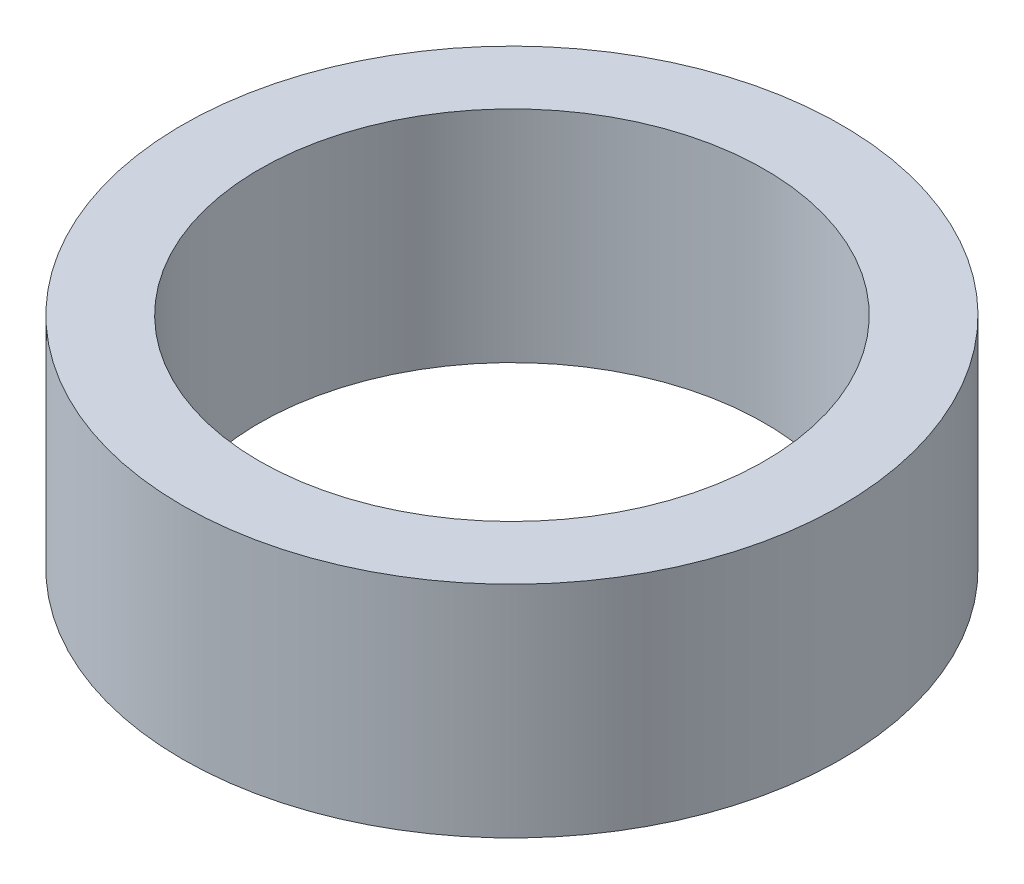
SolidWorks part; units mm, degrees
ref_plane "Front Plane" through (0, 0, 0) normal (0, 0, 1) x (1, 0, 0)
ref_plane "Top Plane" through (0, 0, 0) normal (0, 1, 0) x (1, 0, 0)
ref_plane "Right Plane" through (0, 0, 0) normal (1, 0, 0) x (0, 0, -1)
sketch "Sketch1" plane through (0, 0, 0) normal (0, 1, 0) x (1, 0, 0)
  circle A0 centre (0, 0) radius 19.05
  dimension "D1" = 38.1
extrude "Boss-Extrude1" add sketch "Sketch1" along normal blind 12.7 contours A0
sketch "Sketch4" plane through (0, 12.7, 0) normal (0, 1, 0) x (1, 0, 0)
  circle A0 centre (0, 0) radius 14.605
  dimension "D1" = 29.21
extrude "Cut-Extrude1" cut sketch "Sketch4" against normal through all
